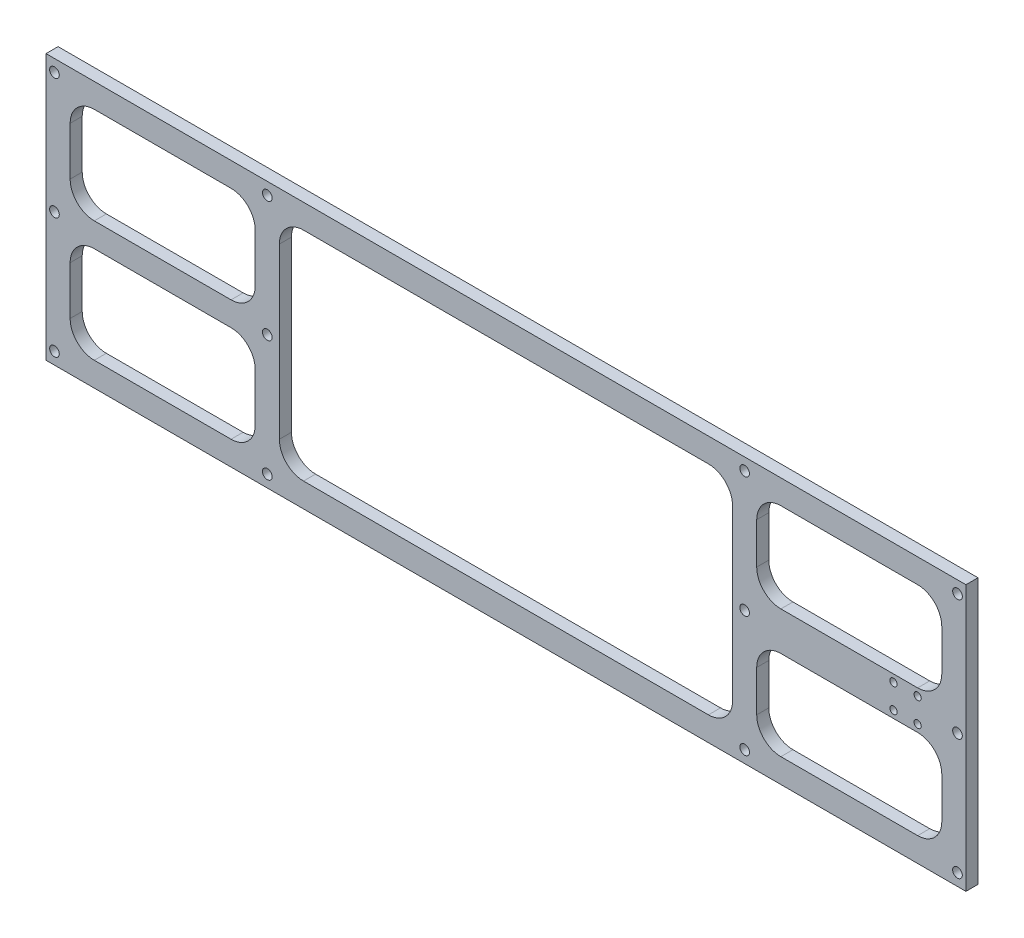
SolidWorks part; units mm, degrees
ref_plane "前视基准面" through (0, 0, 0) normal (0, 0, 1) x (1, 0, 0)
ref_plane "上视基准面" through (0, 0, 0) normal (0, 1, 0) x (1, 0, 0)
ref_plane "右视基准面" through (0, 0, 0) normal (1, 0, 0) x (0, 0, -1)
sketch "草图1" plane through (0, 0, 0) normal (0, 0, 1) x (1, 0, 0)
  line L1 (0, 0) -> (381, 0)
  line L2 (0, 0) -> (0, 110)
  line L3 (0, 110) -> (381, 110)
  line L4 (381, 0) -> (381, 110)
  dimension "D1" = 381
  dimension "D2" = 110
extrude "凸台-拉伸1" add sketch "草图1" along normal blind 5
sketch "草图2" plane through (0, 0, 5) normal (0, 0, 1) x (1, 0, 0)
  line L0 (0, 0) -> (381, 0) construction
  line L1 (381, 110) -> (0, 110) construction
  line L2 (0, 110) -> (0, 0) construction
  line L3 (381, 0) -> (381, 110) construction
  circle A0 centre (3.5, 105) radius 2
  circle A1 centre (3.5, 55) radius 2
  circle A2 centre (3.5, 5) radius 2
  circle A3 centre (377.5, 105) radius 2
  circle A4 centre (377.5, 55) radius 2
  circle A5 centre (377.5, 5) radius 2
  circle A6 centre (91.65, 105) radius 2
  circle A7 centre (91.65, 55) radius 2
  circle A8 centre (91.65, 5) radius 2
  circle A12 centre (289.35, 105) radius 2
  circle A13 centre (289.35, 55) radius 2
  circle A14 centre (289.35, 5) radius 2
  circle A15 centre (-84.65, 105) radius 2 [skipped]
  circle A16 centre (-84.65, 55) radius 2 [skipped]
  circle A17 centre (-84.65, 5) radius 2 [skipped]
  dimension "D1" = 4
  dimension "D2" = 4
  dimension "D3" = 4
  dimension "D4" = 4
  dimension "D5" = 4
  dimension "D6" = 4
  dimension "D13" = 5
  dimension "D14" = 5
  dimension "D7" = 55
  dimension "D8" = 55
  dimension "D9" = 5
  dimension "D10" = 5
  dimension "D11" = 3.5
  dimension "D12" = 3.5
  dimension "D15" = 2
  dimension "D16" = 2
extrude "切除-拉伸1" cut sketch "草图2" against normal blind 5
sketch "草图3" plane through (0, 0, 5) normal (0, 0, 1) x (1, 0, 0)
  line L0 (0, 110) -> (0, 0) construction
  line L1 (20, 100) -> (76.65, 100)
  line L2 (10, 90) -> (10, 70)
  line L3 (20, 60) -> (76.65, 60)
  line L4 (86.65, 90) -> (86.65, 70)
  line L5 (20, 50) -> (76.65, 50)
  line L6 (10, 40) -> (10, 20)
  line L7 (20, 10) -> (76.65, 10)
  line L8 (86.65, 40) -> (86.65, 20)
  line L9 (106.65, 100) -> (274.35, 100)
  line L10 (96.65, 90) -> (96.65, 70)
  line L11 (106.65, 60) -> (274.35, 60)
  line L12 (284.35, 90) -> (284.35, 70)
  line L13 (106.65, 50) -> (274.35, 50)
  line L14 (96.65, 40) -> (96.65, 20)
  line L15 (106.65, 10) -> (274.35, 10)
  line L16 (284.35, 40) -> (284.35, 20)
  line L17 (304.35, 100) -> (361, 100)
  line L18 (294.35, 90) -> (294.35, 73)
  line L19 (304.35, 63) -> (361, 63)
  line L20 (371, 90) -> (371, 73)
  line L21 (304.35, 47) -> (361, 47)
  line L22 (294.35, 37) -> (294.35, 20)
  line L23 (304.35, 10) -> (361, 10)
  line L24 (371, 37) -> (371, 20)
  line L25 (381, 0) -> (381, 110) construction
  line L26 (381, 110) -> (0, 110) construction
  line L27 (0, 0) -> (381, 0) construction
  circle A0 centre (91.65, 5) radius 2 construction
  circle A1 centre (91.65, 55) radius 2 construction
  circle A2 centre (289.35, 55) radius 2 construction
  circle A3 centre (289.35, 5) radius 2 construction
  circle A4 centre (3.5, 55) radius 2 construction
  arc A5 (10, 20) -> (20, 10) centre (20, 20) ccw
  arc A6 (20, 50) -> (10, 40) centre (20, 40) ccw
  arc A7 (76.65, 50) -> (86.65, 40) centre (76.65, 40) cw
  arc A8 (76.65, 10) -> (86.65, 20) centre (76.65, 20) ccw
  arc A9 (96.65, 20) -> (106.65, 10) centre (106.65, 20) ccw
  arc A10 (106.65, 50) -> (96.65, 40) centre (106.65, 40) ccw
  arc A11 (274.35, 50) -> (284.35, 40) centre (274.35, 40) cw
  arc A12 (274.35, 10) -> (284.35, 20) centre (274.35, 20) ccw
  arc A13 (294.35, 20) -> (304.35, 10) centre (304.35, 20) ccw
  arc A14 (361, 10) -> (371, 20) centre (361, 20) ccw
  arc A15 (361, 47) -> (371, 37) centre (361, 37) cw
  arc A16 (304.35, 47) -> (294.35, 37) centre (304.35, 37) ccw
  arc A17 (361, 63) -> (371, 73) centre (361, 73) ccw
  arc A18 (361, 100) -> (371, 90) centre (361, 90) cw
  arc A19 (304.35, 100) -> (294.35, 90) centre (304.35, 90) ccw
  arc A20 (294.35, 73) -> (304.35, 63) centre (304.35, 73) ccw
  arc A21 (274.35, 60) -> (284.35, 70) centre (274.35, 70) ccw
  arc A22 (274.35, 100) -> (284.35, 90) centre (274.35, 90) cw
  arc A23 (96.65, 70) -> (106.65, 60) centre (106.65, 70) ccw
  arc A24 (106.65, 100) -> (96.65, 90) centre (106.65, 90) ccw
  arc A25 (76.65, 100) -> (86.65, 90) centre (76.65, 90) cw
  arc A26 (76.65, 60) -> (86.65, 70) centre (76.65, 70) ccw
  arc A27 (10, 70) -> (20, 60) centre (20, 70) ccw
  arc A28 (20, 100) -> (10, 90) centre (20, 90) ccw
  dimension "D10" = 5
  dimension "D25" = 10
  dimension "D1" = 10
  dimension "D2" = 10
  dimension "D3" = 10
  dimension "D4" = 10
  dimension "D5" = 10
  dimension "D6" = 10
  dimension "D7" = 10
  dimension "D8" = 10
  dimension "D9" = 5
  dimension "D11" = 5
  dimension "D12" = 5
  dimension "D13" = 10
  dimension "D14" = 10
  dimension "D15" = 10
  dimension "D16" = 10
  dimension "D17" = 10
  dimension "D18" = 10
  dimension "D19" = 10
  dimension "D20" = 10
  dimension "D21" = 16
  dimension "D22" = 5
  dimension "D23" = 5
  dimension "D24" = 8
extrude "切除-拉伸2" cut sketch "草图3" against normal blind 5
sketch "草图6" plane through (0, 0, 0) normal (0, 0, -1) x (-1, 0, 0)
  line L0 (-304.35, 63) -> (-361, 63) construction
  line L1 (-381, 0) -> (-381, 110) construction
  circle A0 centre (-361, 60) radius 1.5
  circle A1 centre (-351, 60) radius 1.5
  circle A2 centre (-361, 50) radius 1.5
  circle A3 centre (-351, 50) radius 1.5
  dimension "D1" = 3
  dimension "D2" = 3
  dimension "D3" = 3
  dimension "D4" = 3
  dimension "D5" = 10
  dimension "D6" = 10
  dimension "D7" = 10
  dimension "D8" = 3
  dimension "D9" = 20
extrude "切除-拉伸3" cut sketch "草图6" against normal blind 5
sketch "草图7" plane through (0, 0, 5) normal (0, 0, 1) x (1, 0, 0)
  line L0 (96.65, 90) -> (96.65, 100)
  line L1 (96.65, 100) -> (284.35, 100)
  line L2 (284.35, 100) -> (284.35, 10)
  line L3 (284.35, 10) -> (96.65, 10)
  line L4 (96.65, 10) -> (96.65, 90)
extrude "切除-拉伸4" cut sketch "草图7" against normal blind 10
fillet "圆角1" radius 10 4 edges at (284.35, 10, 2.5) (284.35, 100, 2.5) (96.65, 100, 2.5) (96.65, 10, 2.5)
